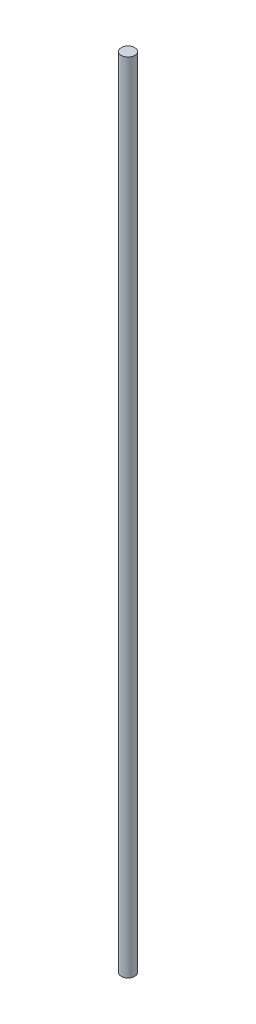
SolidWorks part; units mm, degrees
material "1023 Листовая углеродистая сталь (SS)"
ref_plane "Спереди" through (0, 0, 0) normal (0, 0, 1) x (1, 0, 0)
ref_plane "Сверху" through (0, 0, 0) normal (0, 1, 0) x (1, 0, 0)
ref_plane "Справа" through (0, 0, 0) normal (1, 0, 0) x (0, 0, -1)
sketch "Эскиз1" plane through (0, 0, 0) normal (0, 1, 0) x (1, 0, 0)
  circle A0 centre (0, 0) radius 2
  dimension "D1" = 4
extrude "Бобышка-Вытянуть1" add sketch "Эскиз1" along normal blind 235
